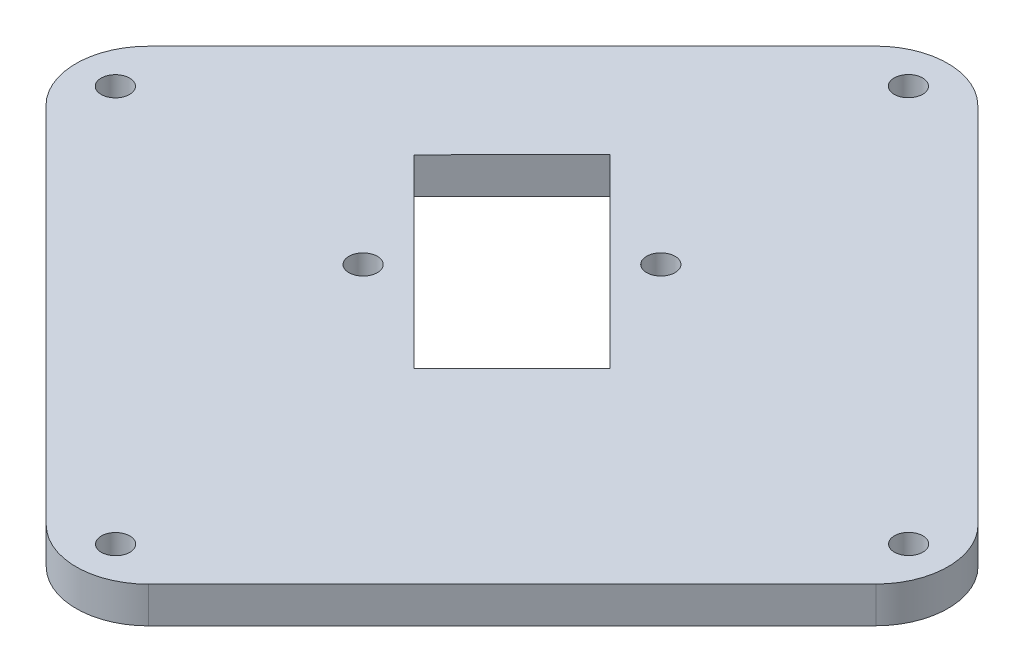
SolidWorks part; units mm, degrees
material "Acrylic (Medium-high impact)"
ref_plane "Front Plane" through (0, 0, 0) normal (0, 0, 1) x (1, 0, 0)
ref_plane "Top Plane" through (0, 0, 0) normal (0, 1, 0) x (1, 0, 0)
ref_plane "Right Plane" through (0, 0, 0) normal (1, 0, 0) x (0, 0, -1)
sketch "Sketch1" plane through (0, 0, 0) normal (0, 1, 0) x (1, 0, 0)
  line L0 (14.9016, -5.0424) -> (-1.3529, 11.2018)
  line L1 (-1.3529, 11.2018) -> (7.2633, 19.8235)
  line L2 (7.2633, 19.8235) -> (23.5178, 3.5793)
  line L3 (23.5178, 3.5793) -> (14.9016, -5.0424)
  line L4 (15.1477, 44.2388) -> (-25.7632, 3.3021)
  line L5 (-25.7632, 3.3021) -> (15.1735, -37.6088)
  line L7 (15.1735, -37.6088) -> (56.0844, 3.3279)
  line L8 (-5.3078, 23.7705) -> (35.6289, -17.1404) construction
  line L26 (35.616, 23.7834) -> (-5.2949, -17.1533) construction
  line L28 (15.1477, 44.2388) -> (56.0844, 3.3279)
  circle A0 centre (17.8401, 13.7083) radius 1.25
  circle A1 centre (4.769, 0.6289) radius 1.25
  circle A2 centre (-19.6694, 3.304) radius 1.25
  circle A3 centre (15.1496, 38.145) radius 1.25
  circle A4 centre (49.9905, 3.326) radius 1.25
  circle A5 centre (15.1715, -31.5149) radius 1.25
  dimension "D8" = 11.176
  dimension "D9" = 2.5
  dimension "D10" = 18.4912
  dimension "D12" = 4.309
  dimension "D13" = 4.309
  dimension "D14" = 4.309
  dimension "D15" = 4.309
  dimension "D17" = 4.309
  dimension "D18" = 4.309
  dimension "D19" = 4.309
  dimension "D2" = 57.875
  dimension "D3" = 57.875
  dimension "D4" = 12.189
  dimension "D5" = 22.98
  dimension "D6" = 6.0945
  dimension "D7" = 23.213
  dimension "D11" = 9.2456
  dimension "D16" = 4.309
extrude "Boss-Extrude1" add sketch "Sketch1" along normal blind 3.175
fillet "Fillet1" radius 6.35 4 edges at (-25.7632, 1.5875, -3.3021) (15.1477, 1.5875, -44.2388) (15.1735, 1.5875, 37.6088) (56.0844, 1.5875, -3.3279)
